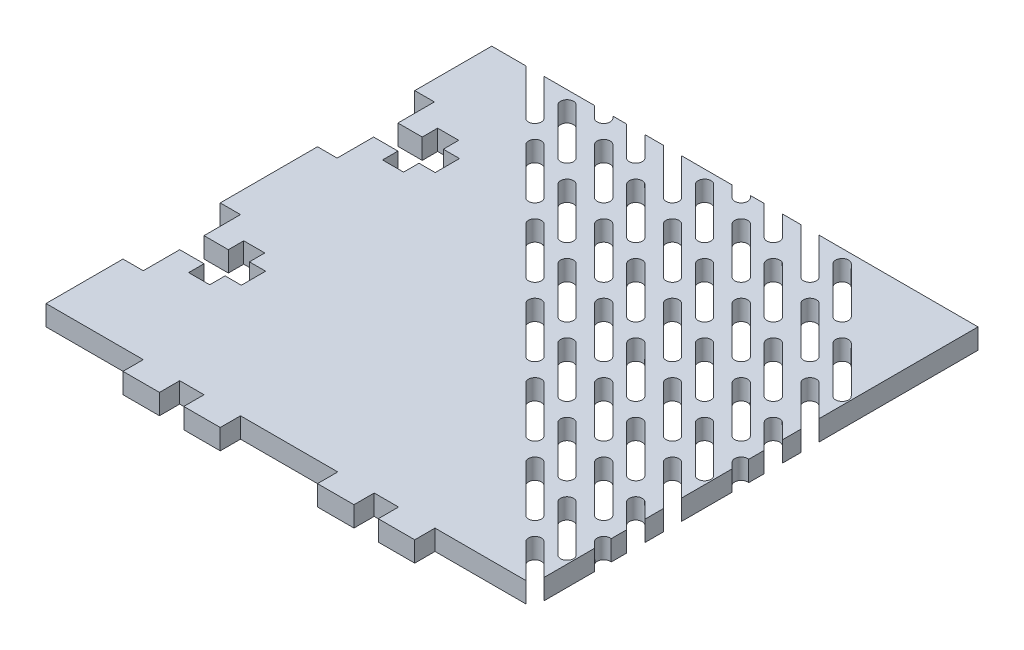
SolidWorks part; units mm, degrees
ref_plane "Front Plane" through (0, 0, 0) normal (0, 0, 1) x (1, 0, 0)
ref_plane "Top Plane" through (0, 0, 0) normal (0, 1, 0) x (1, 0, 0)
ref_plane "Right Plane" through (0, 0, 0) normal (1, 0, 0) x (0, 0, -1)
sketch "Sketch1" plane through (0, 0, 0) normal (0, 1, 0) x (1, 0, 0)
  line L0 (-38.1, 38.1) -> (38.1, -38.1) construction
  line L2 (-38.1, 38.1) -> (-38.1, -38.1) construction
  line L3 (-38.1, -38.1) -> (38.1, -38.1) construction
  line L4 (38.1, 38.1) -> (38.1, -38.1) construction
  line L6 (34.925, 34.925) -> (34.925, -34.925) construction
  line L7 (-34.925, -34.925) -> (34.925, -34.925) construction
  line L8 (-27.813, -13.335) -> (-25.273, -13.335)
  line L9 (22.86, 34.925) -> (-34.925, 34.925)
  line L18 (22.86, 34.925) -> (34.925, 34.925)
  line L20 (-15.24, -38.1) -> (-15.24, -36.5125) construction
  line L22 (7.62, -36.5125) -> (22.86, -36.5125) construction
  line L23 (-22.86, -36.5125) -> (-7.62, -36.5125) construction
  line L24 (15.24, -38.1) -> (15.24, -36.5125) construction
  line L25 (22.86, -34.925) -> (34.925, -34.925)
  line L26 (22.86, -38.1) -> (22.86, -34.925)
  line L27 (22.86, -38.1) -> (17.145, -38.1)
  line L28 (7.62, -34.925) -> (7.62, -38.1)
  line L29 (-7.62, -34.925) -> (7.62, -34.925)
  line L30 (-34.925, 34.925) -> (34.925, 34.925) construction
  line L31 (-7.62, -38.1) -> (-7.62, -34.925)
  line L32 (17.145, -34.925) -> (17.145, -38.1)
  line L33 (-22.86, -34.925) -> (-22.86, -38.1)
  line L34 (-34.925, -34.925) -> (-22.86, -34.925)
  line L35 (-35.0215, 0) -> (34.925, 0) construction
  line L36 (-27.9095, 17.145) -> (-25.3695, 17.145)
  line L37 (-35.0215, 13.335) -> (-35.0215, 17.145) construction
  line L38 (-35.0215, 22.86) -> (-35.0215, 7.62) construction
  line L39 (-35.0215, 13.335) -> (-31.2115, 13.335)
  line L40 (-31.2115, 13.335) -> (-31.2115, 10.922)
  line L41 (-31.2115, 10.922) -> (-27.9095, 10.922)
  line L42 (-27.9095, 10.922) -> (-27.9095, 13.335)
  line L43 (-27.9095, 13.335) -> (-25.3695, 13.335)
  line L44 (-25.3695, 13.335) -> (-25.3695, 17.145)
  line L45 (-35.0215, 15.24) -> (-25.3695, 15.24) construction
  line L46 (-27.9095, 19.558) -> (-27.9095, 17.145)
  line L47 (-31.2115, 17.145) -> (-31.2115, 19.558)
  line L48 (-31.2115, 19.558) -> (-27.9095, 19.558)
  line L49 (-35.0215, 17.145) -> (-31.2115, 17.145)
  line L50 (-34.925, 34.925) -> (-38.1, 34.925)
  line L51 (34.925, 34.925) -> (38.1, 34.925)
  line L52 (-38.1, 34.925) -> (-38.1, 22.86)
  line L53 (-38.1, 22.86) -> (-35.0215, 22.86)
  line L54 (-35.0215, 22.86) -> (-35.0215, 7.62) construction
  line L55 (-35.0215, 7.62) -> (-38.1, 7.62)
  line L56 (-38.1, 7.62) -> (-38.1, -7.62)
  line L57 (-38.1, -7.62) -> (-34.925, -7.62)
  line L58 (-34.925, -7.62) -> (-34.925, -22.86) construction
  line L59 (-34.925, -22.86) -> (-38.1, -22.86)
  line L60 (-38.1, -22.86) -> (-38.1, -34.925)
  line L61 (-38.1, -34.925) -> (-34.925, -34.925)
  line L62 (-34.925, -17.145) -> (-34.925, -13.335) construction
  line L63 (-34.925, 34.925) -> (-34.925, -34.925) construction
  line L64 (-34.925, -17.145) -> (-31.115, -17.145)
  line L65 (-31.115, -17.145) -> (-31.115, -19.558)
  line L66 (-31.115, -19.558) -> (-27.813, -19.558)
  line L67 (-27.813, -19.558) -> (-27.813, -17.145)
  line L68 (-27.813, -17.145) -> (-25.273, -17.145)
  line L69 (-25.273, -17.145) -> (-25.273, -13.335)
  line L70 (-34.925, -15.24) -> (-25.273, -15.24) construction
  line L71 (-27.813, -10.922) -> (-27.813, -13.335)
  line L72 (-31.115, -13.335) -> (-31.115, -10.922)
  line L73 (-31.115, -10.922) -> (-27.813, -10.922)
  line L74 (-34.925, -13.335) -> (-31.115, -13.335)
  line L75 (-34.925, -7.62) -> (-34.925, -13.335)
  line L76 (-34.925, -17.145) -> (-34.925, -22.86)
  line L77 (-35.0215, 22.86) -> (-35.0215, 17.145)
  line L78 (-35.0215, 13.335) -> (-35.0215, 7.62)
  line L79 (0, 38.1) -> (0, -34.925) construction
  line L80 (38.1, 34.925) -> (38.1, -22.86)
  line L81 (38.1, -22.86) -> (38.1, -34.925)
  line L120 (34.925, -34.925) -> (38.1, -34.925)
  line L130 (17.145, -34.925) -> (13.335, -34.925)
  line L131 (13.335, -38.1) -> (7.62, -38.1)
  line L132 (13.335, -34.925) -> (13.335, -38.1)
  line L133 (-13.335, -38.1) -> (-7.62, -38.1)
  line L134 (-13.335, -34.925) -> (-13.335, -38.1)
  line L135 (-17.145, -34.925) -> (-13.335, -34.925)
  line L136 (-17.145, -34.925) -> (-17.145, -38.1)
  line L137 (-22.86, -38.1) -> (-17.145, -38.1)
  line L138 (-38.1, 38.1) -> (38.1, 38.1) construction
  point P4 (0, 0)
  point P43 (-35.0215, 15.24)
  dimension "D2" = 76.2
  dimension "D3" = 76.2
  dimension "D4" = 15.24
  dimension "D5" = 12.065
  dimension "D7" = 3.302
  dimension "D8" = 1.905
  dimension "D9" = 3.81
  dimension "D10" = 2.54
  dimension "D13" = 3.302
  dimension "D14" = 1.905
  dimension "D15" = 3.81
  dimension "D16" = 2.54
  dimension "D17" = 4.318
extrude "Boss-Extrude1" add sketch "Sketch1" along normal blind 3.175
sketch "Sketch2" plane through (0, 0, 0) normal (0, -1, 0) x (1, 0, 0)
  line L0 (-32.1195, -35.7116) -> (-24.9353, -28.5274) construction
  line L1 (-32.8379, -34.9932) -> (-25.6537, -27.809)
  line L2 (-31.4011, -36.43) -> (-24.2169, -29.2458)
  line L3 (-38.1, -38.1) -> (38.1, 38.1) construction
  line L4 (-24.2169, -32.8379) -> (-17.0327, -25.6537) construction
  line L5 (-24.9353, -32.1195) -> (-17.7511, -24.9353)
  line L6 (-23.4985, -33.5564) -> (-16.3143, -26.3721)
  line L7 (-28.5274, -32.1195) -> (-23.1393, -26.7314) construction
  line L8 (-23.1393, -26.7314) -> (-20.6248, -29.2458) construction
  line L9 (-17.7511, -21.3432) -> (-12.3629, -15.9551) construction
  line L10 (-12.3629, -15.9551) -> (-9.8485, -18.4695) construction
  line L12 (-21.3432, -24.9353) -> (-14.159, -17.7511) construction
  line L13 (-22.0616, -24.2169) -> (-14.8774, -17.0327)
  line L14 (-20.6248, -25.6537) -> (-13.4406, -18.4695)
  line L15 (-13.4406, -22.0616) -> (-6.2564, -14.8774) construction
  line L16 (-14.159, -21.3432) -> (-6.9748, -14.159)
  line L17 (-12.7222, -22.78) -> (-5.538, -15.5958)
  line L18 (-6.9748, -10.5669) -> (-1.5866, -5.1787) construction
  line L19 (-1.5866, -5.1787) -> (0.9278, -7.6932) construction
  line L20 (-10.5669, -14.159) -> (-3.3827, -6.9748) construction
  line L21 (-11.2853, -13.4406) -> (-4.1011, -6.2564)
  line L22 (-9.8485, -14.8774) -> (-2.6643, -7.6932)
  line L23 (-2.6643, -11.2853) -> (4.5199, -4.1011) construction
  line L24 (-3.3827, -10.5669) -> (3.8015, -3.3827)
  line L25 (-1.9459, -12.0037) -> (5.2384, -4.8195)
  line L26 (3.8015, 0.2094) -> (9.1897, 5.5976) construction
  line L27 (9.1897, 5.5976) -> (11.7041, 3.0831) construction
  line L28 (0.2094, -3.3827) -> (7.3936, 3.8015) construction
  line L29 (-0.509, -2.6643) -> (6.6752, 4.5199)
  line L30 (0.9278, -4.1011) -> (8.112, 3.0831)
  line L31 (8.112, -0.509) -> (15.2962, 6.6752) construction
  line L32 (7.3936, 0.2094) -> (14.5778, 7.3936)
  line L33 (8.8305, -1.2274) -> (16.0147, 5.9568)
  line L34 (14.5778, 10.9857) -> (19.966, 16.3739) construction
  line L35 (19.966, 16.3739) -> (22.4804, 13.8594) construction
  line L36 (10.9857, 7.3936) -> (18.1699, 14.5778) construction
  line L37 (10.2673, 8.112) -> (17.4515, 15.2962)
  line L38 (11.7041, 6.6752) -> (18.8883, 13.8594)
  line L39 (18.8883, 10.2673) -> (26.0725, 17.4515) construction
  line L40 (18.1699, 10.9857) -> (25.3541, 18.1699)
  line L41 (19.6068, 9.5489) -> (26.791, 16.7331)
  line L42 (25.3541, 21.762) -> (30.7423, 27.1502) construction
  line L43 (30.7423, 27.1502) -> (33.2568, 24.6357) construction
  line L44 (21.762, 18.1699) -> (28.9462, 25.3541) construction
  line L45 (21.0436, 18.8883) -> (28.2278, 26.0725)
  line L46 (22.4804, 17.4515) -> (29.6647, 24.6357)
  line L47 (29.6647, 21.0436) -> (36.8489, 28.2278) construction
  line L48 (28.9462, 21.762) -> (36.1304, 28.9462)
  line L49 (30.3831, 20.3252) -> (37.5673, 27.5094)
  line L50 (-12.3629, -26.7314) -> (-6.9748, -21.3432) construction
  line L51 (-6.9748, -21.3432) -> (-4.4603, -23.8577) construction
  line L52 (-15.9551, -30.3235) -> (-8.7708, -23.1393) construction
  line L53 (-16.6735, -29.605) -> (-9.4893, -22.4208)
  line L54 (-15.2366, -31.0419) -> (-8.0524, -23.8577)
  line L55 (-8.0524, -27.4498) -> (-0.8682, -20.2656) construction
  line L56 (-8.7708, -26.7314) -> (-1.5866, -19.5472)
  line L57 (-7.334, -28.1682) -> (-0.1498, -20.984)
  line L58 (-1.5866, -15.9551) -> (3.8015, -10.5669) construction
  line L59 (3.8015, -10.5669) -> (6.316, -13.0814) construction
  line L60 (-5.1787, -19.5472) -> (2.0055, -12.3629) construction
  line L61 (-5.8972, -18.8287) -> (1.287, -11.6445)
  line L62 (-4.4603, -20.2656) -> (2.7239, -13.0814)
  line L63 (2.7239, -16.6735) -> (9.9081, -9.4893) construction
  line L64 (2.0055, -15.9551) -> (9.1897, -8.7708)
  line L65 (3.4423, -17.3919) -> (10.6265, -10.2077)
  line L66 (9.1897, -5.1787) -> (14.5778, 0.2094) construction
  line L67 (14.5778, 0.2094) -> (17.0923, -2.3051) construction
  line L68 (5.5976, -8.7708) -> (12.7818, -1.5866) construction
  line L69 (4.8791, -8.0524) -> (12.0633, -0.8682)
  line L70 (6.316, -9.4893) -> (13.5002, -2.3051)
  line L71 (13.5002, -5.8972) -> (20.6844, 1.287) construction
  line L72 (12.7818, -5.1787) -> (19.966, 2.0055)
  line L73 (14.2186, -6.6156) -> (21.4028, 0.5686)
  line L74 (19.966, 5.5976) -> (25.3541, 10.9857) construction
  line L75 (25.3541, 10.9857) -> (27.8686, 8.4712) construction
  line L76 (16.3739, 2.0055) -> (23.5581, 9.1897) construction
  line L77 (15.6555, 2.7239) -> (22.8397, 9.9081)
  line L78 (17.0923, 1.287) -> (24.2765, 8.4712)
  line L79 (24.2765, 4.8791) -> (31.4607, 12.0633) construction
  line L80 (23.5581, 5.5976) -> (30.7423, 12.7818)
  line L81 (24.9949, 4.1607) -> (32.1791, 11.3449)
  line L82 (30.7423, 16.3739) -> (36.1304, 21.762) construction
  line L83 (36.1304, 21.762) -> (38.6449, 19.2476) construction
  line L84 (27.1502, 12.7818) -> (34.3344, 19.966) construction
  line L85 (26.4318, 13.5002) -> (33.616, 20.6844)
  line L86 (27.8686, 12.0633) -> (35.0528, 19.2476)
  line L87 (35.0528, 15.6555) -> (42.237, 22.8397) construction
  line L88 (34.3344, 16.3739) -> (41.5186, 23.5581)
  line L89 (35.7712, 14.937) -> (42.9554, 22.1212)
  line L90 (-6.9748, -32.1195) -> (-1.5866, -26.7314) construction
  line L91 (-1.5866, -26.7314) -> (0.9278, -29.2458) construction
  line L92 (-10.5669, -35.7116) -> (-3.3827, -28.5274) construction
  line L93 (-11.2853, -34.9932) -> (-4.1011, -27.809)
  line L94 (-9.8485, -36.43) -> (-2.6643, -29.2458)
  line L95 (-2.6643, -32.8379) -> (4.5199, -25.6537) construction
  line L96 (-3.3827, -32.1195) -> (3.8015, -24.9353)
  line L97 (-1.9459, -33.5564) -> (5.2384, -26.3721)
  line L98 (3.8015, -21.3432) -> (9.1897, -15.9551) construction
  line L99 (9.1897, -15.9551) -> (11.7041, -18.4695) construction
  line L100 (0.2094, -24.9353) -> (7.3936, -17.7511) construction
  line L101 (-0.509, -24.2169) -> (6.6752, -17.0327)
  line L102 (0.9278, -25.6537) -> (8.112, -18.4695)
  line L103 (8.112, -22.0616) -> (15.2962, -14.8774) construction
  line L104 (7.3936, -21.3432) -> (14.5778, -14.159)
  line L105 (8.8305, -22.78) -> (16.0147, -15.5958)
  line L106 (14.5778, -10.5669) -> (19.966, -5.1787) construction
  line L107 (19.966, -5.1787) -> (22.4804, -7.6932) construction
  line L108 (10.9857, -14.159) -> (18.1699, -6.9748) construction
  line L109 (10.2673, -13.4406) -> (17.4515, -6.2564)
  line L110 (11.7041, -14.8774) -> (18.8883, -7.6932)
  line L111 (18.8883, -11.2853) -> (26.0725, -4.1011) construction
  line L112 (18.1699, -10.5669) -> (25.3541, -3.3827)
  line L113 (19.6068, -12.0037) -> (26.791, -4.8195)
  line L114 (25.3541, 0.2094) -> (30.7423, 5.5976) construction
  line L115 (30.7423, 5.5976) -> (33.2568, 3.0831) construction
  line L116 (21.762, -3.3827) -> (28.9462, 3.8015) construction
  line L117 (21.0436, -2.6643) -> (28.2278, 4.5199)
  line L118 (22.4804, -4.1011) -> (29.6647, 3.0831)
  line L119 (29.6647, -0.509) -> (36.8489, 6.6752) construction
  line L120 (28.9462, 0.2094) -> (36.1304, 7.3936)
  line L121 (30.3831, -1.2274) -> (37.5673, 5.9568)
  line L122 (36.1304, 10.9857) -> (41.5186, 16.3739) construction
  line L123 (41.5186, 16.3739) -> (44.0331, 13.8594) construction
  line L124 (32.5383, 7.3936) -> (39.7225, 14.5778) construction
  line L125 (31.8199, 8.112) -> (39.0041, 15.2962)
  line L126 (33.2568, 6.6752) -> (40.441, 13.8594)
  line L127 (40.441, 10.2673) -> (47.6252, 17.4515) construction
  line L128 (39.7225, 10.9857) -> (46.9067, 18.1699)
  line L129 (41.1594, 9.5489) -> (48.3436, 16.7331)
  line L130 (-1.5866, -37.5077) -> (3.8015, -32.1195) construction
  line L131 (3.8015, -32.1195) -> (6.316, -34.634) construction
  line L132 (-5.1787, -41.0998) -> (2.0055, -33.9156) construction
  line L133 (-5.8972, -40.3813) -> (1.287, -33.1971)
  line L134 (-4.4603, -41.8182) -> (2.7239, -34.634)
  line L135 (2.7239, -38.2261) -> (9.9081, -31.0419) construction
  line L136 (2.0055, -37.5077) -> (9.1897, -30.3235)
  line L137 (3.4423, -38.9445) -> (10.6265, -31.7603)
  line L138 (9.1897, -26.7314) -> (14.5778, -21.3432) construction
  line L139 (14.5778, -21.3432) -> (17.0923, -23.8577) construction
  line L140 (5.5976, -30.3235) -> (12.7818, -23.1393) construction
  line L141 (4.8791, -29.605) -> (12.0633, -22.4208)
  line L142 (6.316, -31.0419) -> (13.5002, -23.8577)
  line L143 (13.5002, -27.4498) -> (20.6844, -20.2656) construction
  line L144 (12.7818, -26.7314) -> (19.966, -19.5472)
  line L145 (14.2186, -28.1682) -> (21.4028, -20.984)
  line L146 (19.966, -15.9551) -> (25.3541, -10.5669) construction
  line L147 (25.3541, -10.5669) -> (27.8686, -13.0814) construction
  line L148 (16.3739, -19.5472) -> (23.5581, -12.3629) construction
  line L149 (15.6555, -18.8287) -> (22.8397, -11.6445)
  line L150 (17.0923, -20.2656) -> (24.2765, -13.0814)
  line L151 (24.2765, -16.6735) -> (31.4607, -9.4893) construction
  line L152 (23.5581, -15.9551) -> (30.7423, -8.7708)
  line L153 (24.9949, -17.3919) -> (32.1791, -10.2077)
  line L154 (30.7423, -5.1787) -> (36.1304, 0.2094) construction
  line L155 (36.1304, 0.2094) -> (38.6449, -2.3051) construction
  line L156 (27.1502, -8.7708) -> (34.3344, -1.5866) construction
  line L157 (26.4318, -8.0524) -> (33.616, -0.8682)
  line L158 (27.8686, -9.4893) -> (35.0528, -2.3051)
  line L159 (35.0528, -5.8972) -> (42.237, 1.287) construction
  line L160 (34.3344, -5.1787) -> (41.5186, 2.0055)
  line L161 (35.7712, -6.6156) -> (42.9554, 0.5686)
  line L162 (41.5186, 5.5976) -> (46.9067, 10.9857) construction
  line L163 (46.9067, 10.9857) -> (49.4212, 8.4712) construction
  line L164 (37.9265, 2.0055) -> (45.1107, 9.1897) construction
  line L165 (37.2081, 2.7239) -> (44.3923, 9.9081)
  line L166 (38.6449, 1.287) -> (45.8291, 8.4712)
  line L167 (45.8291, 4.8791) -> (53.0133, 12.0633) construction
  line L168 (45.1107, 5.5976) -> (52.2949, 12.7818)
  line L169 (46.5475, 4.1607) -> (53.7317, 11.3449)
  line L170 (3.8015, -42.8958) -> (9.1897, -37.5077) construction
  line L171 (9.1897, -37.5077) -> (11.7041, -40.0221) construction
  line L172 (0.2094, -46.4879) -> (7.3936, -39.3037) construction
  line L173 (-0.509, -45.7695) -> (6.6752, -38.5853)
  line L174 (0.9278, -47.2063) -> (8.112, -40.0221)
  line L175 (8.112, -43.6142) -> (15.2962, -36.43) construction
  line L176 (7.3936, -42.8958) -> (14.5778, -35.7116)
  line L177 (8.8305, -44.3327) -> (16.0147, -37.1485)
  line L178 (14.5778, -32.1195) -> (19.966, -26.7314) construction
  line L179 (19.966, -26.7314) -> (22.4804, -29.2458) construction
  line L180 (10.9857, -35.7116) -> (18.1699, -28.5274) construction
  line L181 (10.2673, -34.9932) -> (17.4515, -27.809)
  line L182 (11.7041, -36.43) -> (18.8883, -29.2458)
  line L183 (18.8883, -32.8379) -> (26.0725, -25.6537) construction
  line L184 (18.1699, -32.1195) -> (25.3541, -24.9353)
  line L185 (19.6068, -33.5564) -> (26.791, -26.3721)
  line L186 (25.3541, -21.3432) -> (30.7423, -15.9551) construction
  line L187 (30.7423, -15.9551) -> (33.2568, -18.4695) construction
  line L188 (21.762, -24.9353) -> (28.9462, -17.7511) construction
  line L189 (21.0436, -24.2169) -> (28.2278, -17.0327)
  line L190 (22.4804, -25.6537) -> (29.6647, -18.4695)
  line L191 (29.6647, -22.0616) -> (36.8489, -14.8774) construction
  line L192 (28.9462, -21.3432) -> (36.1304, -14.159)
  line L193 (30.3831, -22.78) -> (37.5673, -15.5958)
  line L194 (36.1304, -10.5669) -> (41.5186, -5.1787) construction
  line L195 (41.5186, -5.1787) -> (44.0331, -7.6932) construction
  line L196 (32.5383, -14.159) -> (39.7225, -6.9748) construction
  line L197 (31.8199, -13.4406) -> (39.0041, -6.2564)
  line L198 (33.2568, -14.8774) -> (40.441, -7.6932)
  line L199 (40.441, -11.2853) -> (47.6252, -4.1011) construction
  line L200 (39.7225, -10.5669) -> (46.9067, -3.3827)
  line L201 (41.1594, -12.0037) -> (48.3436, -4.8195)
  line L202 (46.9067, 0.2094) -> (52.2949, 5.5976) construction
  line L203 (52.2949, 5.5976) -> (54.8094, 3.0831) construction
  line L204 (43.3146, -3.3827) -> (50.4988, 3.8015) construction
  line L205 (42.5962, -2.6643) -> (49.7804, 4.5199)
  line L206 (44.0331, -4.1011) -> (51.2173, 3.0831)
  line L207 (51.2173, -0.509) -> (58.4015, 6.6752) construction
  line L208 (50.4988, 0.2094) -> (57.683, 7.3936)
  line L209 (51.9357, -1.2274) -> (59.1199, 5.9568)
  line L210 (-23.1393, -37.5077) -> (-17.7511, -32.1195) construction
  line L211 (-17.7511, -32.1195) -> (-15.2366, -34.634) construction
  line L212 (-26.7314, -41.0998) -> (-19.5472, -33.9156) construction
  line L213 (-27.4498, -40.3813) -> (-20.2656, -33.1971)
  line L214 (-26.0129, -41.8182) -> (-18.8287, -34.634)
  line L215 (-18.8287, -38.2261) -> (-11.6445, -31.0419) construction
  line L216 (-19.5472, -37.5077) -> (-12.3629, -30.3235)
  line L217 (-18.1103, -38.9445) -> (-10.9261, -31.7603)
  line L218 (-17.7511, -42.8958) -> (-12.3629, -37.5077) construction
  line L219 (-12.3629, -37.5077) -> (-9.8485, -40.0221) construction
  line L220 (-21.3432, -46.4879) -> (-14.159, -39.3037) construction
  line L221 (-22.0616, -45.7695) -> (-14.8774, -38.5853)
  line L222 (-20.6248, -47.2063) -> (-13.4406, -40.0221)
  line L223 (-13.4406, -43.6142) -> (-6.2564, -36.43) construction
  line L224 (-14.159, -42.8958) -> (-6.9748, -35.7116)
  line L225 (-12.7222, -44.3327) -> (-5.538, -37.1485)
  line L226 (-12.3629, -48.284) -> (-6.9748, -42.8958) construction
  line L227 (-6.9748, -42.8958) -> (-4.4603, -45.4103) construction
  line L228 (-15.9551, -51.8761) -> (-8.7708, -44.6919) construction
  line L229 (-16.6735, -51.1577) -> (-9.4893, -43.9735)
  line L230 (-15.2366, -52.5945) -> (-8.0524, -45.4103)
  line L231 (-8.0524, -49.0024) -> (-0.8682, -41.8182) construction
  line L232 (-8.7708, -48.284) -> (-1.5866, -41.0998)
  line L233 (-7.334, -49.7208) -> (-0.1498, -42.5366)
  line L234 (-6.9748, -53.6721) -> (-1.5866, -48.284) construction
  line L235 (-1.5866, -48.284) -> (0.9278, -50.7984) construction
  line L236 (-10.5669, -57.2642) -> (-3.3827, -50.08) construction
  line L237 (-11.2853, -56.5458) -> (-4.1011, -49.3616)
  line L238 (-9.8485, -57.9826) -> (-2.6643, -50.7984)
  line L239 (-2.6643, -54.3905) -> (4.5199, -47.2063) construction
  line L240 (-3.3827, -53.6721) -> (3.8015, -46.4879)
  line L241 (-1.9459, -55.109) -> (5.2384, -47.9248)
  line L242 (36.1304, 32.5383) -> (41.5186, 37.9265) construction
  line L243 (41.5186, 37.9265) -> (44.0331, 35.412) construction
  line L244 (32.5383, 28.9462) -> (39.7225, 36.1304) construction
  line L245 (31.8199, 29.6647) -> (39.0041, 36.8489)
  line L246 (33.2568, 28.2278) -> (40.441, 35.412)
  line L247 (40.441, 31.8199) -> (47.6252, 39.0041) construction
  line L248 (39.7225, 32.5383) -> (46.9067, 39.7225)
  line L249 (41.1594, 31.1015) -> (48.3436, 38.2857)
  line L250 (41.5186, 27.1502) -> (46.9067, 32.5383) construction
  line L251 (46.9067, 32.5383) -> (49.4212, 30.0239) construction
  line L252 (37.9265, 23.5581) -> (45.1107, 30.7423) construction
  line L253 (37.2081, 24.2765) -> (44.3923, 31.4607)
  line L254 (38.6449, 22.8397) -> (45.8291, 30.0239)
  line L255 (45.8291, 26.4318) -> (53.0133, 33.616) construction
  line L256 (45.1107, 27.1502) -> (52.2949, 34.3344)
  line L257 (46.5475, 25.7133) -> (53.7317, 32.8975)
  line L258 (46.9067, 21.762) -> (52.2949, 27.1502) construction
  line L259 (52.2949, 27.1502) -> (54.8094, 24.6357) construction
  line L260 (43.3146, 18.1699) -> (50.4988, 25.3541) construction
  line L261 (42.5962, 18.8883) -> (49.7804, 26.0725)
  line L262 (44.0331, 17.4515) -> (51.2173, 24.6357)
  line L263 (51.2173, 21.0436) -> (58.4015, 28.2278) construction
  line L264 (50.4988, 21.762) -> (57.683, 28.9462)
  line L265 (51.9357, 20.3252) -> (59.1199, 27.5094)
  line L266 (52.2949, 16.3739) -> (57.683, 21.762) construction
  line L267 (57.683, 21.762) -> (60.1975, 19.2476) construction
  line L268 (48.7028, 12.7818) -> (55.887, 19.966) construction
  line L269 (47.9844, 13.5002) -> (55.1686, 20.6844)
  line L270 (49.4212, 12.0633) -> (56.6054, 19.2476)
  line L271 (56.6054, 15.6555) -> (63.7896, 22.8397) construction
  line L272 (55.887, 16.3739) -> (63.0712, 23.5581)
  line L273 (57.3238, 14.937) -> (64.508, 22.1212)
  line L274 (57.683, 10.9857) -> (63.0712, 16.3739) construction
  line L275 (63.0712, 16.3739) -> (65.5857, 13.8594) construction
  line L276 (54.0909, 7.3936) -> (61.2752, 14.5778) construction
  line L277 (53.3725, 8.112) -> (60.5567, 15.2962)
  line L278 (54.8094, 6.6752) -> (61.9936, 13.8594)
  line L279 (61.9936, 10.2673) -> (69.1778, 17.4515) construction
  line L280 (61.2752, 10.9857) -> (68.4594, 18.1699)
  line L281 (62.712, 9.5489) -> (69.8962, 16.7331)
  arc A0 (-32.8379, -34.9932) -> (-31.4011, -36.43) centre (-32.1195, -35.7116) ccw
  arc A1 (-24.2169, -29.2458) -> (-25.6537, -27.809) centre (-24.9353, -28.5274) ccw
  arc A2 (-24.9353, -32.1195) -> (-23.4985, -33.5564) centre (-24.2169, -32.8379) ccw
  arc A3 (-16.3143, -26.3721) -> (-17.7511, -24.9353) centre (-17.0327, -25.6537) ccw
  arc A4 (-22.0616, -24.2169) -> (-20.6248, -25.6537) centre (-21.3432, -24.9353) ccw
  arc A5 (-13.4406, -18.4695) -> (-14.8774, -17.0327) centre (-14.159, -17.7511) ccw
  arc A6 (-14.159, -21.3432) -> (-12.7222, -22.78) centre (-13.4406, -22.0616) ccw
  arc A7 (-5.538, -15.5958) -> (-6.9748, -14.159) centre (-6.2564, -14.8774) ccw
  arc A8 (-11.2853, -13.4406) -> (-9.8485, -14.8774) centre (-10.5669, -14.159) ccw
  arc A9 (-2.6643, -7.6932) -> (-4.1011, -6.2564) centre (-3.3827, -6.9748) ccw
  arc A10 (-3.3827, -10.5669) -> (-1.9459, -12.0037) centre (-2.6643, -11.2853) ccw
  arc A11 (5.2384, -4.8195) -> (3.8015, -3.3827) centre (4.5199, -4.1011) ccw
  arc A12 (-0.509, -2.6643) -> (0.9278, -4.1011) centre (0.2094, -3.3827) ccw
  arc A13 (8.112, 3.0831) -> (6.6752, 4.5199) centre (7.3936, 3.8015) ccw
  arc A14 (7.3936, 0.2094) -> (8.8305, -1.2274) centre (8.112, -0.509) ccw
  arc A15 (16.0147, 5.9568) -> (14.5778, 7.3936) centre (15.2962, 6.6752) ccw
  arc A16 (10.2673, 8.112) -> (11.7041, 6.6752) centre (10.9857, 7.3936) ccw
  arc A17 (18.8883, 13.8594) -> (17.4515, 15.2962) centre (18.1699, 14.5778) ccw
  arc A18 (18.1699, 10.9857) -> (19.6068, 9.5489) centre (18.8883, 10.2673) ccw
  arc A19 (26.791, 16.7331) -> (25.3541, 18.1699) centre (26.0725, 17.4515) ccw
  arc A20 (21.0436, 18.8883) -> (22.4804, 17.4515) centre (21.762, 18.1699) ccw
  arc A21 (29.6647, 24.6357) -> (28.2278, 26.0725) centre (28.9462, 25.3541) ccw
  arc A22 (28.9462, 21.762) -> (30.3831, 20.3252) centre (29.6647, 21.0436) ccw
  arc A23 (37.5673, 27.5094) -> (36.1304, 28.9462) centre (36.8489, 28.2278) ccw
  arc A24 (-16.6735, -29.605) -> (-15.2366, -31.0419) centre (-15.9551, -30.3235) ccw
  arc A25 (-8.0524, -23.8577) -> (-9.4893, -22.4208) centre (-8.7708, -23.1393) ccw
  arc A26 (-8.7708, -26.7314) -> (-7.334, -28.1682) centre (-8.0524, -27.4498) ccw
  arc A27 (-0.1498, -20.984) -> (-1.5866, -19.5472) centre (-0.8682, -20.2656) ccw
  arc A28 (-5.8972, -18.8287) -> (-4.4603, -20.2656) centre (-5.1787, -19.5472) ccw
  arc A29 (2.7239, -13.0814) -> (1.287, -11.6445) centre (2.0055, -12.3629) ccw
  arc A30 (2.0055, -15.9551) -> (3.4423, -17.3919) centre (2.7239, -16.6735) ccw
  arc A31 (10.6265, -10.2077) -> (9.1897, -8.7708) centre (9.9081, -9.4893) ccw
  arc A32 (4.8791, -8.0524) -> (6.316, -9.4893) centre (5.5976, -8.7708) ccw
  arc A33 (13.5002, -2.3051) -> (12.0633, -0.8682) centre (12.7818, -1.5866) ccw
  arc A34 (12.7818, -5.1787) -> (14.2186, -6.6156) centre (13.5002, -5.8972) ccw
  arc A35 (21.4028, 0.5686) -> (19.966, 2.0055) centre (20.6844, 1.287) ccw
  arc A36 (15.6555, 2.7239) -> (17.0923, 1.287) centre (16.3739, 2.0055) ccw
  arc A37 (24.2765, 8.4712) -> (22.8397, 9.9081) centre (23.5581, 9.1897) ccw
  arc A38 (23.5581, 5.5976) -> (24.9949, 4.1607) centre (24.2765, 4.8791) ccw
  arc A39 (32.1791, 11.3449) -> (30.7423, 12.7818) centre (31.4607, 12.0633) ccw
  arc A40 (26.4318, 13.5002) -> (27.8686, 12.0633) centre (27.1502, 12.7818) ccw
  arc A41 (35.0528, 19.2476) -> (33.616, 20.6844) centre (34.3344, 19.966) ccw
  arc A42 (34.3344, 16.3739) -> (35.7712, 14.937) centre (35.0528, 15.6555) ccw
  arc A43 (42.9554, 22.1212) -> (41.5186, 23.5581) centre (42.237, 22.8397) ccw
  arc A44 (-11.2853, -34.9932) -> (-9.8485, -36.43) centre (-10.5669, -35.7116) ccw
  arc A45 (-2.6643, -29.2458) -> (-4.1011, -27.809) centre (-3.3827, -28.5274) ccw
  arc A46 (-3.3827, -32.1195) -> (-1.9459, -33.5564) centre (-2.6643, -32.8379) ccw
  arc A47 (5.2384, -26.3721) -> (3.8015, -24.9353) centre (4.5199, -25.6537) ccw
  arc A48 (-0.509, -24.2169) -> (0.9278, -25.6537) centre (0.2094, -24.9353) ccw
  arc A49 (8.112, -18.4695) -> (6.6752, -17.0327) centre (7.3936, -17.7511) ccw
  arc A50 (7.3936, -21.3432) -> (8.8305, -22.78) centre (8.112, -22.0616) ccw
  arc A51 (16.0147, -15.5958) -> (14.5778, -14.159) centre (15.2962, -14.8774) ccw
  arc A52 (10.2673, -13.4406) -> (11.7041, -14.8774) centre (10.9857, -14.159) ccw
  arc A53 (18.8883, -7.6932) -> (17.4515, -6.2564) centre (18.1699, -6.9748) ccw
  arc A54 (18.1699, -10.5669) -> (19.6068, -12.0037) centre (18.8883, -11.2853) ccw
  arc A55 (26.791, -4.8195) -> (25.3541, -3.3827) centre (26.0725, -4.1011) ccw
  arc A56 (21.0436, -2.6643) -> (22.4804, -4.1011) centre (21.762, -3.3827) ccw
  arc A57 (29.6647, 3.0831) -> (28.2278, 4.5199) centre (28.9462, 3.8015) ccw
  arc A58 (28.9462, 0.2094) -> (30.3831, -1.2274) centre (29.6647, -0.509) ccw
  arc A59 (37.5673, 5.9568) -> (36.1304, 7.3936) centre (36.8489, 6.6752) ccw
  arc A60 (31.8199, 8.112) -> (33.2568, 6.6752) centre (32.5383, 7.3936) ccw
  arc A61 (40.441, 13.8594) -> (39.0041, 15.2962) centre (39.7225, 14.5778) ccw
  arc A62 (39.7225, 10.9857) -> (41.1594, 9.5489) centre (40.441, 10.2673) ccw
  arc A63 (48.3436, 16.7331) -> (46.9067, 18.1699) centre (47.6252, 17.4515) ccw
  arc A64 (-5.8972, -40.3813) -> (-4.4603, -41.8182) centre (-5.1787, -41.0998) ccw
  arc A65 (2.7239, -34.634) -> (1.287, -33.1971) centre (2.0055, -33.9156) ccw
  arc A66 (2.0055, -37.5077) -> (3.4423, -38.9445) centre (2.7239, -38.2261) ccw
  arc A67 (10.6265, -31.7603) -> (9.1897, -30.3235) centre (9.9081, -31.0419) ccw
  arc A68 (4.8791, -29.605) -> (6.316, -31.0419) centre (5.5976, -30.3235) ccw
  arc A69 (13.5002, -23.8577) -> (12.0633, -22.4208) centre (12.7818, -23.1393) ccw
  arc A70 (12.7818, -26.7314) -> (14.2186, -28.1682) centre (13.5002, -27.4498) ccw
  arc A71 (21.4028, -20.984) -> (19.966, -19.5472) centre (20.6844, -20.2656) ccw
  arc A72 (15.6555, -18.8287) -> (17.0923, -20.2656) centre (16.3739, -19.5472) ccw
  arc A73 (24.2765, -13.0814) -> (22.8397, -11.6445) centre (23.5581, -12.3629) ccw
  arc A74 (23.5581, -15.9551) -> (24.9949, -17.3919) centre (24.2765, -16.6735) ccw
  arc A75 (32.1791, -10.2077) -> (30.7423, -8.7708) centre (31.4607, -9.4893) ccw
  arc A76 (26.4318, -8.0524) -> (27.8686, -9.4893) centre (27.1502, -8.7708) ccw
  arc A77 (35.0528, -2.3051) -> (33.616, -0.8682) centre (34.3344, -1.5866) ccw
  arc A78 (34.3344, -5.1787) -> (35.7712, -6.6156) centre (35.0528, -5.8972) ccw
  arc A79 (42.9554, 0.5686) -> (41.5186, 2.0055) centre (42.237, 1.287) ccw
  arc A80 (37.2081, 2.7239) -> (38.6449, 1.287) centre (37.9265, 2.0055) ccw
  arc A81 (45.8291, 8.4712) -> (44.3923, 9.9081) centre (45.1107, 9.1897) ccw
  arc A82 (45.1107, 5.5976) -> (46.5475, 4.1607) centre (45.8291, 4.8791) ccw
  arc A83 (53.7317, 11.3449) -> (52.2949, 12.7818) centre (53.0133, 12.0633) ccw
  arc A84 (-0.509, -45.7695) -> (0.9278, -47.2063) centre (0.2094, -46.4879) ccw
  arc A85 (8.112, -40.0221) -> (6.6752, -38.5853) centre (7.3936, -39.3037) ccw
  arc A86 (7.3936, -42.8958) -> (8.8305, -44.3327) centre (8.112, -43.6142) ccw
  arc A87 (16.0147, -37.1485) -> (14.5778, -35.7116) centre (15.2962, -36.43) ccw
  arc A88 (10.2673, -34.9932) -> (11.7041, -36.43) centre (10.9857, -35.7116) ccw
  arc A89 (18.8883, -29.2458) -> (17.4515, -27.809) centre (18.1699, -28.5274) ccw
  arc A90 (18.1699, -32.1195) -> (19.6068, -33.5564) centre (18.8883, -32.8379) ccw
  arc A91 (26.791, -26.3721) -> (25.3541, -24.9353) centre (26.0725, -25.6537) ccw
  arc A92 (21.0436, -24.2169) -> (22.4804, -25.6537) centre (21.762, -24.9353) ccw
  arc A93 (29.6647, -18.4695) -> (28.2278, -17.0327) centre (28.9462, -17.7511) ccw
  arc A94 (28.9462, -21.3432) -> (30.3831, -22.78) centre (29.6647, -22.0616) ccw
  arc A95 (37.5673, -15.5958) -> (36.1304, -14.159) centre (36.8489, -14.8774) ccw
  arc A96 (31.8199, -13.4406) -> (33.2568, -14.8774) centre (32.5383, -14.159) ccw
  arc A97 (40.441, -7.6932) -> (39.0041, -6.2564) centre (39.7225, -6.9748) ccw
  arc A98 (39.7225, -10.5669) -> (41.1594, -12.0037) centre (40.441, -11.2853) ccw
  arc A99 (48.3436, -4.8195) -> (46.9067, -3.3827) centre (47.6252, -4.1011) ccw
  arc A100 (42.5962, -2.6643) -> (44.0331, -4.1011) centre (43.3146, -3.3827) ccw
  arc A101 (51.2173, 3.0831) -> (49.7804, 4.5199) centre (50.4988, 3.8015) ccw
  arc A102 (50.4988, 0.2094) -> (51.9357, -1.2274) centre (51.2173, -0.509) ccw
  arc A103 (59.1199, 5.9568) -> (57.683, 7.3936) centre (58.4015, 6.6752) ccw
  arc A104 (-27.4498, -40.3813) -> (-26.0129, -41.8182) centre (-26.7314, -41.0998) ccw
  arc A105 (-18.8287, -34.634) -> (-20.2656, -33.1971) centre (-19.5472, -33.9156) ccw
  arc A106 (-19.5472, -37.5077) -> (-18.1103, -38.9445) centre (-18.8287, -38.2261) ccw
  arc A107 (-10.9261, -31.7603) -> (-12.3629, -30.3235) centre (-11.6445, -31.0419) ccw
  arc A108 (-22.0616, -45.7695) -> (-20.6248, -47.2063) centre (-21.3432, -46.4879) ccw
  arc A109 (-13.4406, -40.0221) -> (-14.8774, -38.5853) centre (-14.159, -39.3037) ccw
  arc A110 (-14.159, -42.8958) -> (-12.7222, -44.3327) centre (-13.4406, -43.6142) ccw
  arc A111 (-5.538, -37.1485) -> (-6.9748, -35.7116) centre (-6.2564, -36.43) ccw
  arc A112 (-16.6735, -51.1577) -> (-15.2366, -52.5945) centre (-15.9551, -51.8761) ccw
  arc A113 (-8.0524, -45.4103) -> (-9.4893, -43.9735) centre (-8.7708, -44.6919) ccw
  arc A114 (-8.7708, -48.284) -> (-7.334, -49.7208) centre (-8.0524, -49.0024) ccw
  arc A115 (-0.1498, -42.5366) -> (-1.5866, -41.0998) centre (-0.8682, -41.8182) ccw
  arc A116 (-11.2853, -56.5458) -> (-9.8485, -57.9826) centre (-10.5669, -57.2642) ccw
  arc A117 (-2.6643, -50.7984) -> (-4.1011, -49.3616) centre (-3.3827, -50.08) ccw
  arc A118 (-3.3827, -53.6721) -> (-1.9459, -55.109) centre (-2.6643, -54.3905) ccw
  arc A119 (5.2384, -47.9248) -> (3.8015, -46.4879) centre (4.5199, -47.2063) ccw
  arc A120 (31.8199, 29.6647) -> (33.2568, 28.2278) centre (32.5383, 28.9462) ccw
  arc A121 (40.441, 35.412) -> (39.0041, 36.8489) centre (39.7225, 36.1304) ccw
  arc A122 (39.7225, 32.5383) -> (41.1594, 31.1015) centre (40.441, 31.8199) ccw
  arc A123 (48.3436, 38.2857) -> (46.9067, 39.7225) centre (47.6252, 39.0041) ccw
  arc A124 (37.2081, 24.2765) -> (38.6449, 22.8397) centre (37.9265, 23.5581) ccw
  arc A125 (45.8291, 30.0239) -> (44.3923, 31.4607) centre (45.1107, 30.7423) ccw
  arc A126 (45.1107, 27.1502) -> (46.5475, 25.7133) centre (45.8291, 26.4318) ccw
  arc A127 (53.7317, 32.8975) -> (52.2949, 34.3344) centre (53.0133, 33.616) ccw
  arc A128 (42.5962, 18.8883) -> (44.0331, 17.4515) centre (43.3146, 18.1699) ccw
  arc A129 (51.2173, 24.6357) -> (49.7804, 26.0725) centre (50.4988, 25.3541) ccw
  arc A130 (50.4988, 21.762) -> (51.9357, 20.3252) centre (51.2173, 21.0436) ccw
  arc A131 (59.1199, 27.5094) -> (57.683, 28.9462) centre (58.4015, 28.2278) ccw
  arc A132 (47.9844, 13.5002) -> (49.4212, 12.0633) centre (48.7028, 12.7818) ccw
  arc A133 (56.6054, 19.2476) -> (55.1686, 20.6844) centre (55.887, 19.966) ccw
  arc A134 (55.887, 16.3739) -> (57.3238, 14.937) centre (56.6054, 15.6555) ccw
  arc A135 (64.508, 22.1212) -> (63.0712, 23.5581) centre (63.7896, 22.8397) ccw
  arc A136 (53.3725, 8.112) -> (54.8094, 6.6752) centre (54.0909, 7.3936) ccw
  arc A137 (61.9936, 13.8594) -> (60.5567, 15.2962) centre (61.2752, 14.5778) ccw
  arc A138 (61.2752, 10.9857) -> (62.712, 9.5489) centre (61.9936, 10.2673) ccw
  arc A139 (69.8962, 16.7331) -> (68.4594, 18.1699) centre (69.1778, 17.4515) ccw
  point P2 (-28.5274, -32.1195)
  point P11 (-20.6248, -29.2458)
  point P26 (-17.7511, -21.3432)
  point P33 (-9.8485, -18.4695)
  point P43 (-6.9748, -10.5669)
  point P50 (0.9278, -7.6932)
  point P60 (3.8015, 0.2094)
  point P67 (11.7041, 3.0831)
  point P77 (14.5778, 10.9857)
  point P84 (22.4804, 13.8594)
  point P94 (25.3541, 21.762)
  point P101 (33.2568, 24.6357)
  point P111 (-12.3629, -26.7314)
  point P118 (-4.4603, -23.8577)
  point P128 (-1.5866, -15.9551)
  point P135 (6.316, -13.0814)
  point P145 (9.1897, -5.1787)
  point P152 (17.0923, -2.3051)
  point P162 (19.966, 5.5976)
  point P169 (27.8686, 8.4712)
  point P179 (30.7423, 16.3739)
  point P186 (38.6449, 19.2476)
  point P196 (-6.9748, -32.1195)
  point P203 (0.9278, -29.2458)
  point P213 (3.8015, -21.3432)
  point P220 (11.7041, -18.4695)
  point P230 (14.5778, -10.5669)
  point P237 (22.4804, -7.6932)
  point P247 (25.3541, 0.2094)
  point P254 (33.2568, 3.0831)
  point P264 (36.1304, 10.9857)
  point P271 (44.0331, 13.8594)
  point P281 (-1.5866, -37.5077)
  point P288 (6.316, -34.634)
  point P298 (9.1897, -26.7314)
  point P305 (17.0923, -23.8577)
  point P315 (19.966, -15.9551)
  point P322 (27.8686, -13.0814)
  point P332 (30.7423, -5.1787)
  point P339 (38.6449, -2.3051)
  point P349 (41.5186, 5.5976)
  point P356 (49.4212, 8.4712)
  point P366 (3.8015, -42.8958)
  point P373 (11.7041, -40.0221)
  point P383 (14.5778, -32.1195)
  point P390 (22.4804, -29.2458)
  point P400 (25.3541, -21.3432)
  point P407 (33.2568, -18.4695)
  point P417 (36.1304, -10.5669)
  point P424 (44.0331, -7.6932)
  point P434 (46.9067, 0.2094)
  point P441 (54.8094, 3.0831)
  point P451 (-23.1393, -37.5077)
  point P458 (-15.2366, -34.634)
  point P468 (-17.7511, -42.8958)
  point P475 (-9.8485, -40.0221)
  point P485 (-12.3629, -48.284)
  point P492 (-4.4603, -45.4103)
  point P502 (-6.9748, -53.6721)
  point P509 (0.9278, -50.7984)
  point P519 (36.1304, 32.5383)
  point P526 (44.0331, 35.412)
  point P536 (41.5186, 27.1502)
  point P543 (49.4212, 30.0239)
  point P553 (46.9067, 21.762)
  point P560 (54.8094, 24.6357)
  point P570 (52.2949, 16.3739)
  point P577 (60.1975, 19.2476)
  point P587 (57.683, 10.9857)
  point P594 (65.5857, 13.8594)
  dimension "D1" = 2.032
  dimension "D2" = 10.16
  dimension "D3" = 2.54
  dimension "D4" = 2.032
  dimension "D5" = 10.16
  dimension "D6" = 3.556
  dimension "D7" = 7.62
  dimension "D8" = 3.556
  dimension "D9" = 7
  dimension "D10" = 5
extrude "Cut-Extrude1" cut sketch "Sketch2" against normal through all
